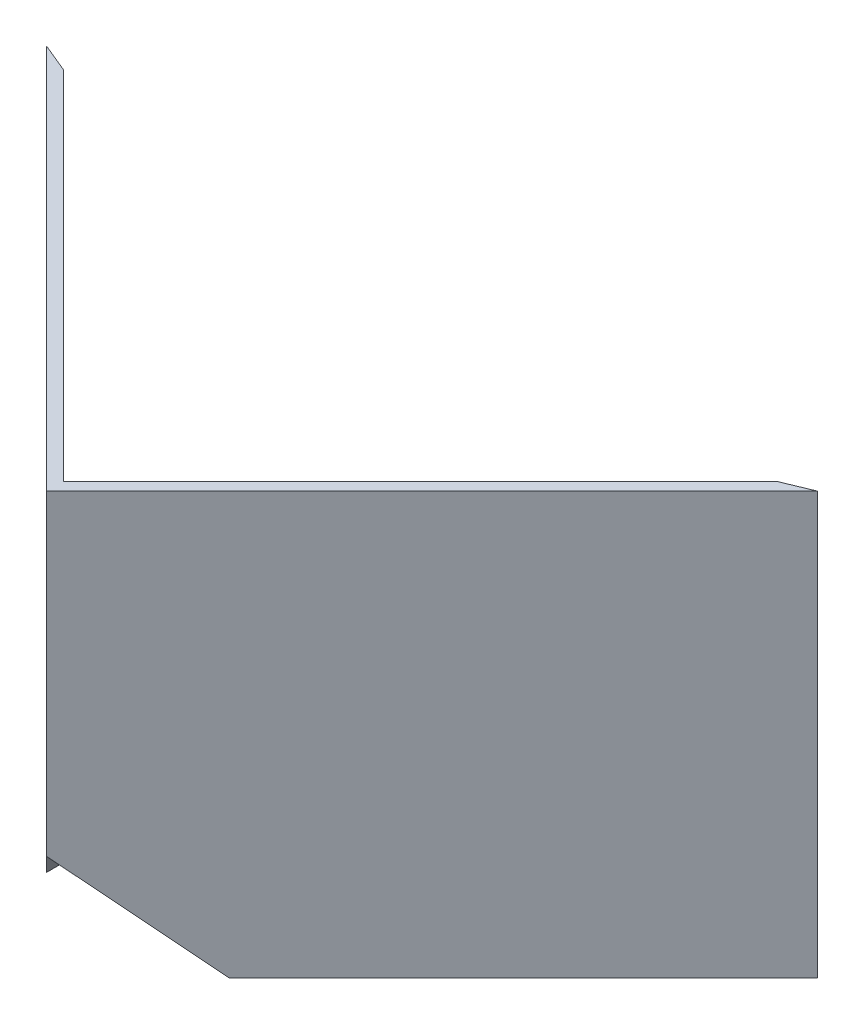
SolidWorks part; units mm, degrees
material "AISI 304"
ref_plane "Front Plane" through (0, 0, 0) normal (0, 0, 1) x (1, 0, 0)
ref_plane "Top Plane" through (0, 0, 0) normal (0, 1, 0) x (1, 0, 0)
ref_plane "Right Plane" through (0, 0, 0) normal (1, 0, 0) x (0, 0, -1)
sketch "Sketch1" plane through (0, 0, 0) normal (0, 1, 0) x (1, 0, 0)
  line L0 (0, -61.1716) -> (-59.1716, -2)
  line L2 (64, 0) -> (0, -64)
  line L3 (0, -64) -> (-64, 0)
  line L5 (59.1716, -2) -> (0, -61.1716)
  line L6 (-59.1716, -2) -> (59.1716, -2) construction
  line L7 (-64, 0) -> (64, 0) construction
  line L8 (64, 0) -> (59.1716, -2)
  line L9 (-59.1716, -2) -> (-64, 0)
  dimension "D1" = 2
extrude "Boss-Extrude1" add sketch "Sketch1" along normal mid plane 70
ref_plane "Plane1" through (0, 0, 61.17) normal (0, 0, 1) x (1, 0, 0)
sketch "Sketch4" plane through (0, 0, 61.17) normal (0, 0, 1) x (1, 0, 0)
  line L0 (-15.18, -35) -> (15.18, -35)
  line L1 (0, -35) -> (64, -35) construction
  line L3 (-64, -35) -> (0, -35) construction
  line L4 (-15.18, -35) -> (0, -17.5)
  line L5 (0, 35) -> (0, -35) construction
  line L6 (0, -17.5) -> (15.18, -35)
  dimension "D4" = 23.1664
  dimension "D5" = 23.1664
extrude "Cut-Extrude3" cut sketch "Sketch4" against normal through all both and the other way through all
